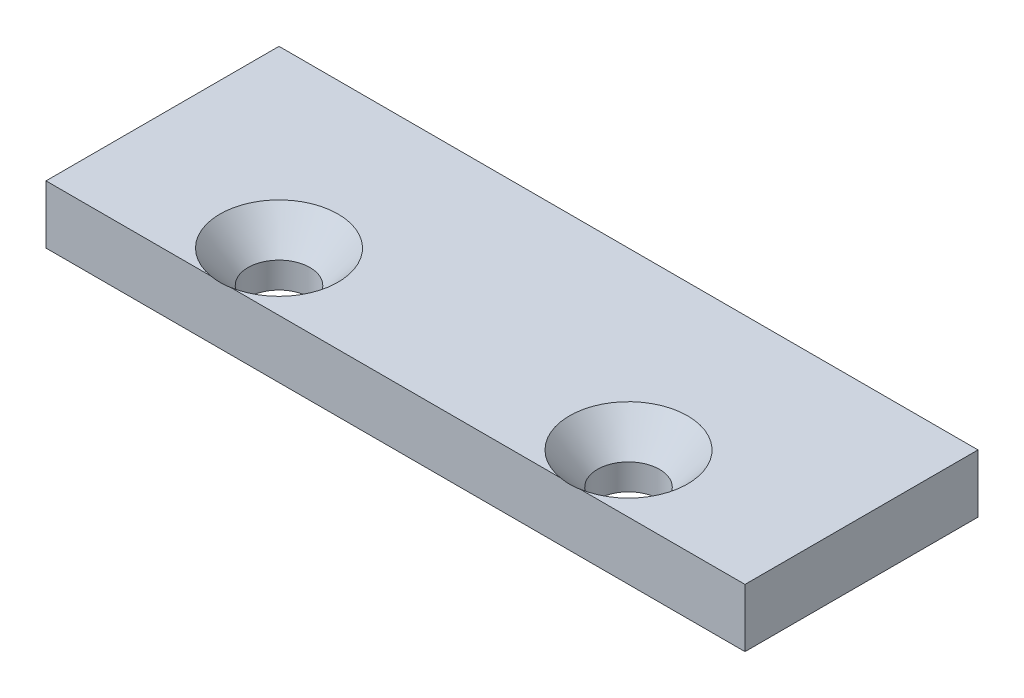
SolidWorks part; units mm, degrees
material "6061 Alloy"
ref_plane "Front Plane" through (0, 0, 0) normal (0, 0, 1) x (1, 0, 0)
ref_plane "Top Plane" through (0, 0, 0) normal (0, 1, 0) x (1, 0, 0)
ref_plane "Right Plane" through (0, 0, 0) normal (1, 0, 0) x (0, 0, -1)
sketch "Sketch1" plane through (0, 0, 0) normal (0, 1, 0) x (1, 0, 0)
  line L1 (0, 0) -> (76.2, 0)
  line L2 (0, 0) -> (0, 25.4)
  line L3 (0, 25.4) -> (76.2, 25.4)
  line L4 (76.2, 0) -> (76.2, 25.4)
  point P5 (57.15, 9.525)
  point P8 (19.05, 9.525)
  dimension "D1" = 25.4
  dimension "D2" = 76.2
  dimension "D3" = 19.05
  dimension "D4" = 9.525
  dimension "D5" = 19.05
  dimension "D6" = 9.525
extrude "Boss-Extrude1" add sketch "Sketch1" against normal blind 6.35
hole_wizard "CSK for 1/4 Flat Head Machine Screw1" positions "Sketch2" profile "Sketch3" countersink size "1/4" standard "ANSI Inch" end condition through all
sketch "Sketch2" plane through (0, 0, 0) normal (0, 1, 0) x (1, 0, 0)
  line L0 (0, 0) -> (76.2, 0) construction
  line L1 (0, 25.4) -> (0, 0) construction
  line L2 (76.2, 0) -> (76.2, 25.4) construction
  point P0 (19.05, 6.35)
  point P2 (57.15, 6.35)
  dimension "D1" = 6.35
  dimension "D2" = 6.35
  dimension "D3" = 19.05
  dimension "D4" = 19.05
sketch "Sketch3" plane through (19.05, 0, -6.35) normal (1, 0, 0) x (0, 0, 1)
  line L0 (0, 0) -> (0, 6.35)
  line L1 (0, 6.35) -> (3.3782, 6.35)
  line L2 (3.3782, 6.35) -> (3.3782, 3.5209)
  line L3 (3.3782, 3.5209) -> (6.4389, 0)
  line L5 (6.4389, 0) -> (0, 0)
  line L6 (-3.3782, 3.5209) -> (-6.4389, 0) construction
  line L11 (0, -6.35) -> (0, 107.95) construction
  dimension "Thru Hole Dia." = 6.7564
  dimension "Thru Hole Depth" = 6.35
  dimension "Near C'Sink Dia." = 12.8778
  dimension "Near C'Sink Angle" = 82
